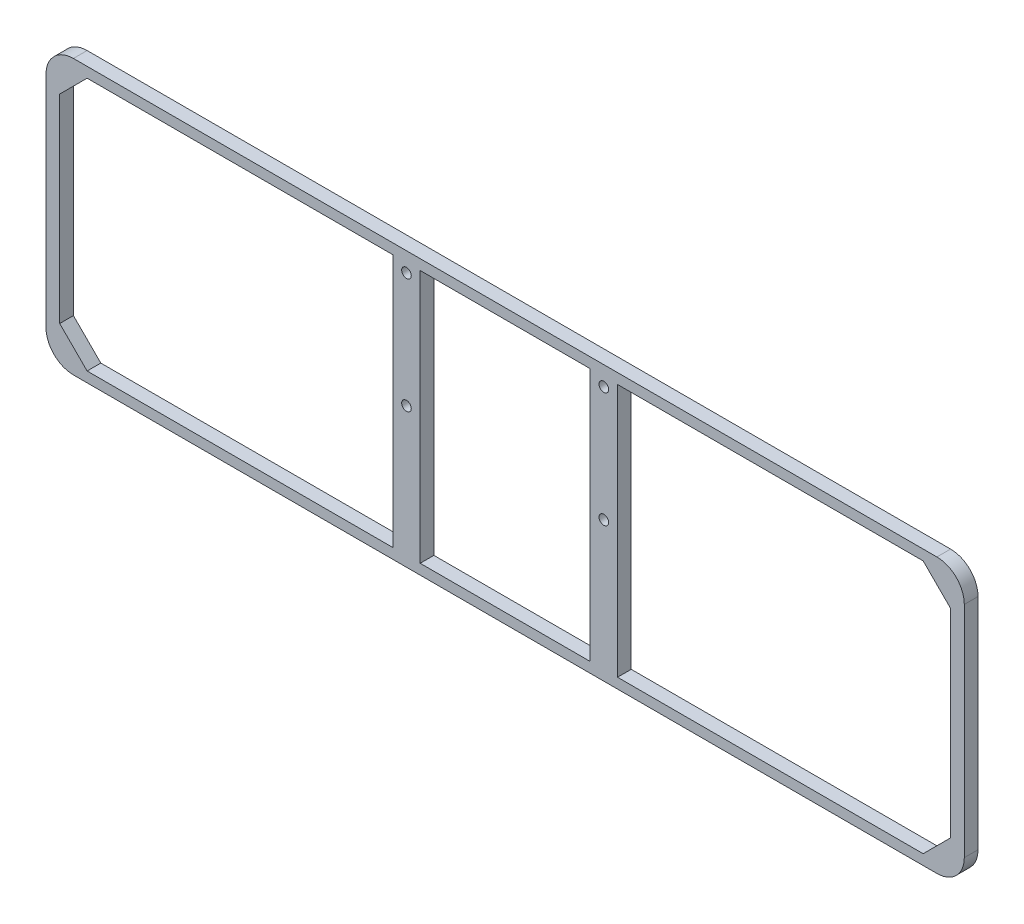
SolidWorks part; units mm, degrees
ref_plane "Front Plane" through (0, 0, 0) normal (0, 0, 1) x (1, 0, 0)
ref_plane "Top Plane" through (0, 0, 0) normal (0, 1, 0) x (1, 0, 0)
ref_plane "Right Plane" through (0, 0, 0) normal (1, 0, 0) x (0, 0, -1)
sketch "Sketch1" plane through (0, 0, 0) normal (0, 0, 1) x (1, 0, 0)
  line L0 (-31, 46.25) -> (31, 46.25)
  line L1 (-167.5, -50) -> (167.5, -50)
  line L2 (-167.5, -50) -> (-167.5, 50)
  line L3 (-167.5, 50) -> (167.5, 50)
  line L4 (167.5, -50) -> (167.5, 50)
  line L5 (-167.5, -50) -> (167.5, 50) construction
  line L6 (-167.5, 50) -> (167.5, -50) construction
  line L7 (-162.5, -46.25) -> (-41, -46.25)
  line L8 (-162.5, -46.25) -> (-162.5, 46.25)
  line L9 (-162.5, 46.25) -> (-41, 46.25)
  line L10 (162.5, -46.25) -> (162.5, 46.25)
  line L11 (-162.5, -46.25) -> (162.5, 46.25) construction
  line L12 (-162.5, 46.25) -> (162.5, -46.25) construction
  line L14 (-41, -46.25) -> (-41, 46.25)
  line L16 (-31, -46.25) -> (-31, 46.25)
  line L22 (31, 46.25) -> (31, -46.25)
  line L24 (41, 46.25) -> (41, -46.25)
  line L25 (-31, -46.25) -> (31, -46.25)
  line L26 (41, -46.25) -> (162.5, -46.25)
  line L27 (41, 46.25) -> (162.5, 46.25)
  circle A0 centre (-36, 43) radius 1.75
  circle A1 centre (36, 43) radius 1.75
  circle A2 centre (36, 1) radius 1.75
  circle A3 centre (-36, 1) radius 1.75
  point P0 (0, 0)
  point P6 (0, 0)
  dimension "D9" = 36
  dimension "D1" = 335
  dimension "D2" = 100
  dimension "D3" = 325
  dimension "D4" = 92.5
  dimension "D5" = 10
  dimension "D6" = 10
  dimension "D7" = 62
  dimension "D8" = 31
  dimension "D12" = 43
  dimension "D10" = 2
  dimension "D11" = 2
extrude "Boss-Extrude1" add sketch "Sketch1" against normal blind 5
fillet "Fillet1" radius 10 4 edges at (167.5, -50, -2.5) (167.5, 50, -2.5) (-167.5, 50, -2.5) (-167.5, -50, -2.5)
chamfer "Chamfer1" distance 10 angle 45 4 edges at (162.5, -46.25, -2.5) (162.5, 46.25, -2.5) (-162.5, 46.25, -2.5) (-162.5, -46.25, -2.5)
